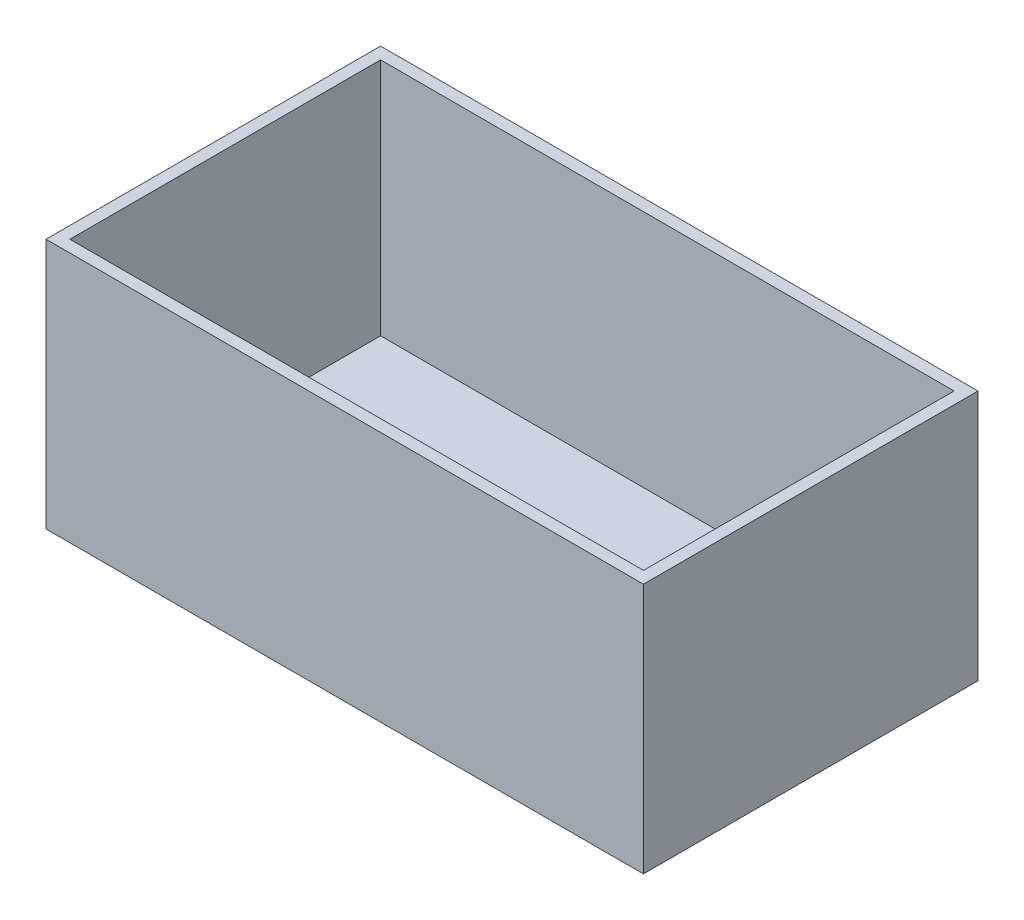
SolidWorks part; units mm, degrees
ref_plane "Front Plane" through (0, 0, 0) normal (0, 0, 1) x (1, 0, 0)
ref_plane "Top Plane" through (0, 0, 0) normal (0, 1, 0) x (1, 0, 0)
ref_plane "Right Plane" through (0, 0, 0) normal (1, 0, 0) x (0, 0, -1)
sketch "Sketch1" plane through (0, 0, 0) normal (0, 1, 0) x (1, 0, 0)
  line L1 (-85.3448, 44.7737) -> (64.6552, 44.7737)
  line L2 (-85.3448, 44.7737) -> (-85.3448, -39.2263)
  line L3 (-85.3448, -39.2263) -> (64.6552, -39.2263)
  line L4 (64.6552, 44.7737) -> (64.6552, -39.2263)
  dimension "D1" = 150
  dimension "D2" = 84
extrude "Boss-Extrude1" add sketch "Sketch1" against normal blind 63
shell "Shell1" thickness 3
